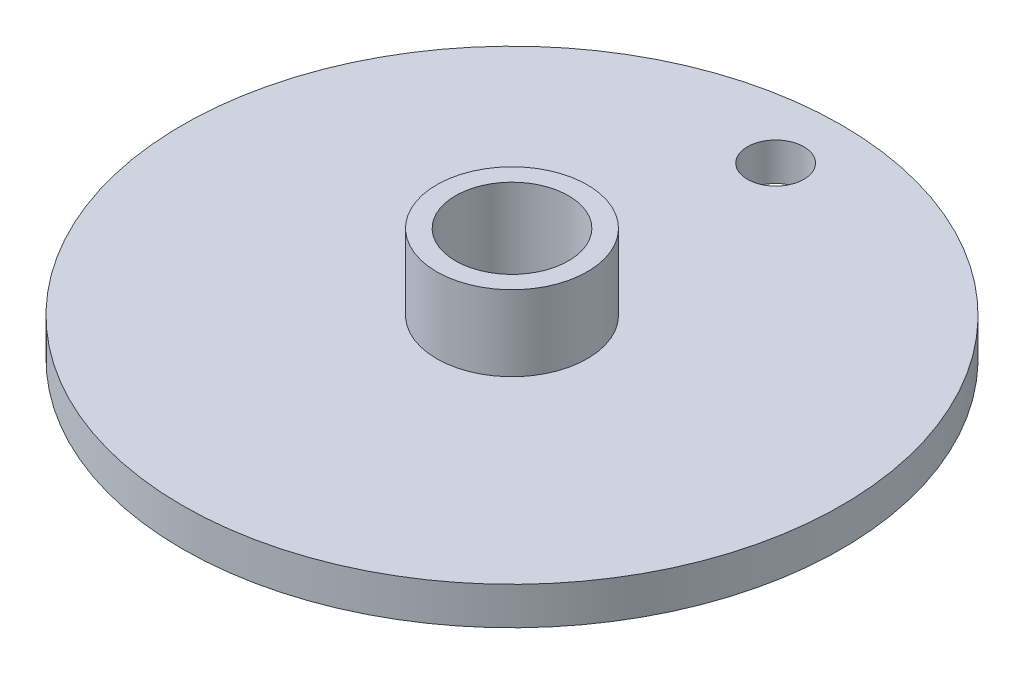
SolidWorks part; units mm, degrees
ref_plane "Front" through (0, 0, 0) normal (0, 0, 1) x (1, 0, 0)
ref_plane "Top" through (0, 0, 0) normal (0, 1, 0) x (1, 0, 0)
ref_plane "Right" through (0, 0, 0) normal (1, 0, 0) x (0, 0, -1)
sketch "Sketch1" plane through (0, 0, 0) normal (0, 1, 0) x (1, 0, 0)
  circle A0 centre (0, 0) radius 3
  circle A1 centre (0, 0) radius 17.5
  dimension "D1" = 6
  dimension "D2" = 35
extrude "Boss-Extrude1" add sketch "Sketch1" along normal blind 2
sketch "Çizim1" plane through (0, 2, 0) normal (0, 1, 0) x (1, 0, 0)
  circle A0 centre (0, 0) radius 4
  circle A1 centre (0, 0) radius 3
  dimension "D1" = 8
extrude "Yükseklik-Ekstrüzyon1" add sketch "Çizim1" along normal blind 4
sketch "Sketch2" plane through (0, 0, 0) normal (0, -1, 0) x (1, 0, 0)
  circle A0 centre (0, -14) radius 1.5
  circle A1 centre (0, 0) radius 3 construction
  dimension "D1" = 3
  dimension "D2" = 14
extrude "Cut-Extrude1" cut sketch "Sketch2" against normal up to next
